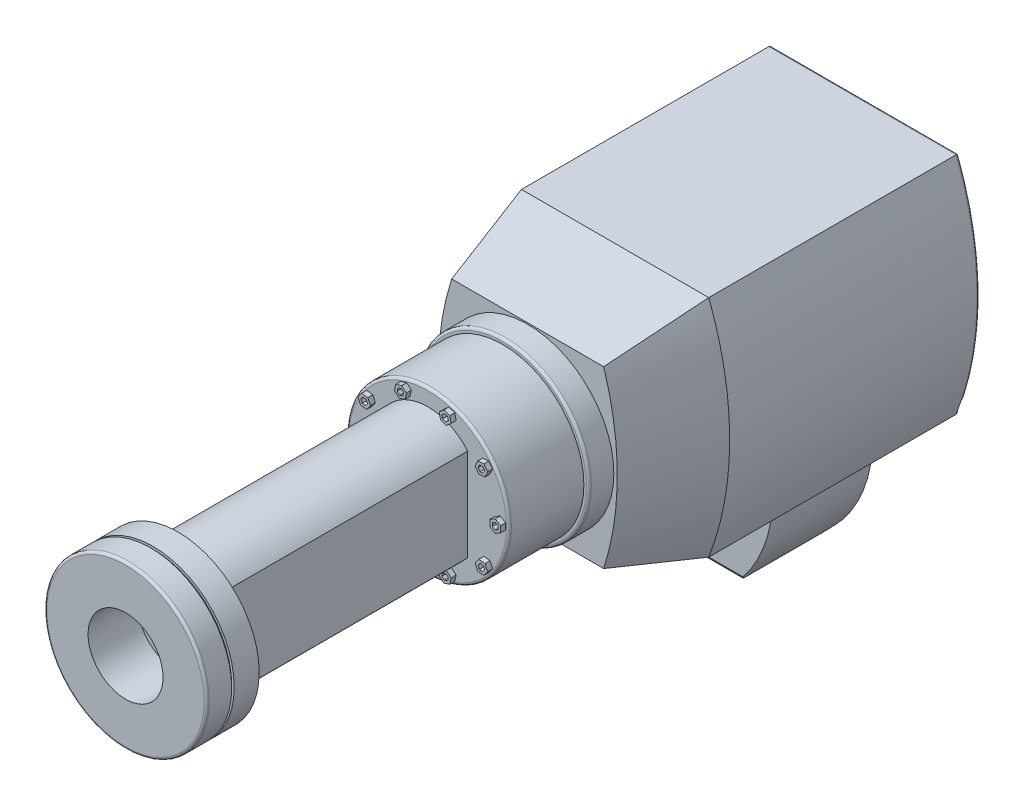
SolidWorks part; units mm, degrees
ref_plane "Front Plane" through (0, 0, 0) normal (0, 0, 1) x (1, 0, 0)
ref_plane "Top Plane" through (0, 0, 0) normal (0, 1, 0) x (1, 0, 0)
ref_plane "Right Plane" through (0, 0, 0) normal (1, 0, 0) x (0, 0, -1)
sketch "Sketch1" plane through (0, 0, 0) normal (0, 0, 1) x (1, 0, 0)
  line L0 (0, 45) -> (0, -45) construction
  line L1 (37.5, 45) -> (-37.5, 45)
  line L2 (37.5, -45) -> (-37.5, -45)
  arc A0 (-37.5, 45) -> (-37.5, -45) centre (79.119, 0) ccw
  arc A1 (37.5, 45) -> (37.5, -45) centre (-79.119, 0) cw
  point P4 (0, 0)
  point P7 (0, 45)
  point P10 (0, -45)
  dimension "D3" = 125
  dimension "D1" = 90
  dimension "D2" = 75
extrude "Boss-Extrude1" add sketch "Sketch1" along normal blind 100
sketch "Sketch2" plane through (0, 0, 100) normal (0, 0, 1) x (1, 0, 0)
  line L2 (-37.5, -45) -> (37.5, -45)
  line L3 (37.5, 45) -> (-37.5, 45)
  line L4 (-37.5, -45) -> (37.5, -45)
  line L5 (37.5, 45) -> (-37.5, 45)
  arc A2 (-37.5, 45) -> (-37.5, -45) centre (79.119, 0) ccw
  arc A3 (37.5, -45) -> (37.5, 45) centre (-79.119, 0) ccw
  arc A4 (-37.5, 45) -> (-37.5, -45) centre (79.119, 0) ccw
  arc A5 (37.5, -45) -> (37.5, 45) centre (-79.119, 0) ccw
  dimension "D1" = 0
ref_plane "Plane1" through (0, 0, 135) normal (0, 0, 1) x (1, 0, 0)
sketch "Sketch3" plane through (0, 0, 135) normal (0, 0, 1) x (1, 0, 0)
  line L7 (-30.4255, -35) -> (30.4255, -35)
  line L8 (30.4255, 35) -> (-30.4255, 35)
  line L9 (-30.4255, -35) -> (30.4255, -35)
  line L10 (30.4255, 35) -> (-30.4255, 35)
  arc A7 (30.4255, -35) -> (30.4255, 35) centre (-79.119, 0) ccw
  arc A8 (-30.4255, 35) -> (-30.4255, -35) centre (79.119, 0) ccw
  arc A9 (30.4255, -35) -> (30.4255, 35) centre (-79.119, 0) ccw
  arc A10 (-30.4255, 35) -> (-30.4255, -35) centre (79.119, 0) ccw
  dimension "D1" = 10
loft "Loft1" add profiles "Sketch3", "Sketch2"
sketch "Sketch4" plane through (0, 0, 135) normal (0, 0, 1) x (1, 0, 0)
  circle A0 centre (0, 0) radius 34.5
  dimension "D1" = 69
extrude "Boss-Extrude2" add sketch "Sketch4" along normal blind 10
sketch "Sketch5" plane through (0, 0, 145) normal (0, 0, 1) x (1, 0, 0)
  circle A2 centre (0, 0) radius 32.5
  circle A3 centre (0, 0) radius 32.5
  dimension "D1" = 2
extrude "Boss-Extrude3" add sketch "Sketch5" along normal blind 30
sketch "Sketch6" plane through (0, 0, 175) normal (0, 0, 1) x (1, 0, 0)
  line L0 (0, 0) -> (29, 0) construction
  line L1 (29, 1.3453) -> (27.8349, 0.6726)
  line L2 (29, -2.5) -> (31.1651, -1.25)
  line L3 (31.1651, -1.25) -> (31.1651, 1.25)
  line L4 (31.1651, 1.25) -> (29, 2.5)
  line L5 (29, 2.5) -> (26.8349, 1.25)
  line L6 (26.8349, 1.25) -> (26.8349, -1.25)
  line L7 (26.8349, -1.25) -> (29, -2.5)
  line L8 (27.8349, 0.6726) -> (27.8349, -0.6726)
  line L9 (27.8349, -0.6726) -> (29, -1.3453)
  line L10 (29, -1.3453) -> (30.1651, -0.6726)
  line L11 (30.1651, -0.6726) -> (30.1651, 0.6726)
  line L12 (30.1651, 0.6726) -> (29, 1.3453)
  circle A0 centre (29, 0) radius 2.1651 construction
  dimension "D1" = 29
  dimension "D2" = 5
  dimension "D3" = 1
extrude "Boss-Extrude4" add sketch "Sketch6" along normal blind 2
pattern_circular "CirPattern1" count 10 over 360 about axis through (0, 0, 0) along (0, 0, 1) of "Boss-Extrude4"
sketch "Sketch7" plane through (0, 0, 175) normal (0, 0, 1) x (1, 0, 0)
  line L0 (0, 0) -> (16, 0) construction
  line L1 (0, -13.0711) -> (0, 23.4073) construction
  line L2 (16, -18.5) -> (16, 18.5)
  line L3 (-16, -18.5) -> (-16, 18.5)
  arc A0 (-16, 18.5) -> (16, 18.5) centre (0, 4.8985) cw
  arc A1 (-16, -18.5) -> (16, -18.5) centre (0, -4.8985) ccw
  point P8 (16, 0)
  dimension "D3" = 21
  dimension "D1" = 16
  dimension "D2" = 37
extrude "Boss-Extrude5" add sketch "Sketch7" along normal blind 100
sketch "Sketch9" plane through (0, 0, 275) normal (0, 0, 1) x (1, 0, 0)
  circle A0 centre (0, 0) radius 32.5 construction
  circle A1 centre (0, 0) radius 32.5
extrude "Boss-Extrude6" add sketch "Sketch9" along normal blind 10
sketch "Sketch10" plane through (0, 0, 285) normal (0, 0, 1) x (1, 0, 0)
  circle A2 centre (0, 0) radius 31.5
  circle A3 centre (0, 0) radius 31.5
  dimension "D1" = 1
extrude "Boss-Extrude7" add sketch "Sketch10" along normal blind 1
sketch "Sketch11" plane through (0, 0, 286) normal (0, 0, 1) x (1, 0, 0)
  circle A0 centre (0, 0) radius 32.5 construction
  circle A1 centre (0, 0) radius 32.5
extrude "Boss-Extrude8" add sketch "Sketch11" along normal blind 10
ref_plane "Plane3" through (-37.5, 0, 0) normal (1, 0, 0) x (0, 0, -1)
sketch "Sketch14" plane through (-37.5, 0, 0) normal (1, 0, 0) x (0, 0, -1)
  line L0 (-100, -45) -> (0, -45) construction
  circle A0 centre (-50, -45) radius 42.5
  dimension "D1" = 85
extrude "Boss-Extrude9" add sketch "Sketch14" along normal mid plane 21
sketch "Sketch15" plane through (-27, 0, 0) normal (1, 0, 0) x (0, 0, -1)
  line L0 (-50, -45) -> (-50, -75) construction
  line L1 (-92.5, -45) -> (-7.5, -45) construction
  line L2 (-70, -45) -> (-70, -75)
  line L3 (-30, -45) -> (-30, -75)
  line L4 (-70, -45) -> (-30, -45)
  arc A0 (-70, -75) -> (-30, -75) centre (-50, -60.3189) ccw
  dimension "D4" = 24.81
  dimension "D1" = 30
  dimension "D2" = 20
  dimension "D3" = 20
extrude "Boss-Extrude10" add sketch "Sketch15" along normal blind 35
ref_plane "Plane4" through (0, 0, 50) normal (0, 0, 1) x (1, 0, 0)
sketch "Sketch16" plane through (0, 0, 50) normal (0, 0, 1) x (1, 0, 0)
  line L0 (8, -87) -> (8, -45)
  line L1 (8, -45) -> (33, -45)
  line L2 (-37.5, -45) -> (37.5, -45) construction
  arc A0 (8, -87) -> (33, -45) centre (-21.8393, -40.7981) ccw
  dimension "D3" = 55
  dimension "D1" = 25
  dimension "D2" = 42
extrude "Boss-Extrude11" add sketch "Sketch16" along normal mid plane 40
sketch "Sketch19" plane through (8, 0, 0) normal (-1, 0, 0) x (0, 0, 1)
  line L3 (70, -87) -> (70, -75)
  line L4 (30, -75) -> (30, -87)
  line L5 (30, -87) -> (70, -87)
  line L6 (70, -87) -> (70, -75)
  line L7 (30, -75) -> (30, -87)
  line L8 (30, -87) -> (70, -87)
  arc A1 (30, -75) -> (70, -75) centre (50, -60.3189) ccw
  arc A2 (30, -75) -> (70, -75) centre (50, -60.3189) ccw
  dimension "D1" = 0
extrude "Cut-Extrude1" cut sketch "Sketch19" against normal through all
fillet "Fillet2" radius 1 9 edges at (0, -45, 0) (45.881, 0, 0) (0, 45, 0) (-45.881, 0, 0) (34.5, 0, 145) (-27, -87.5, 50) (-48, -45, 7.5) (32.5, 0, 175) (32.5, 0, 296)
sketch "Sketch20" plane through (0, 0, 296) normal (0, 0, 1) x (1, 0, 0)
  circle A0 centre (0, 0) radius 15
  dimension "D1" = 30
extrude "Cut-Extrude2" cut sketch "Sketch20" against normal blind 20
sketch "Sketch21" plane through (-48, 0, 0) normal (-1, 0, 0) x (0, 0, 1)
  circle A0 centre (50, -45) radius 15
  dimension "D1" = 30
extrude "Cut-Extrude3" cut sketch "Sketch21" against normal blind 20
